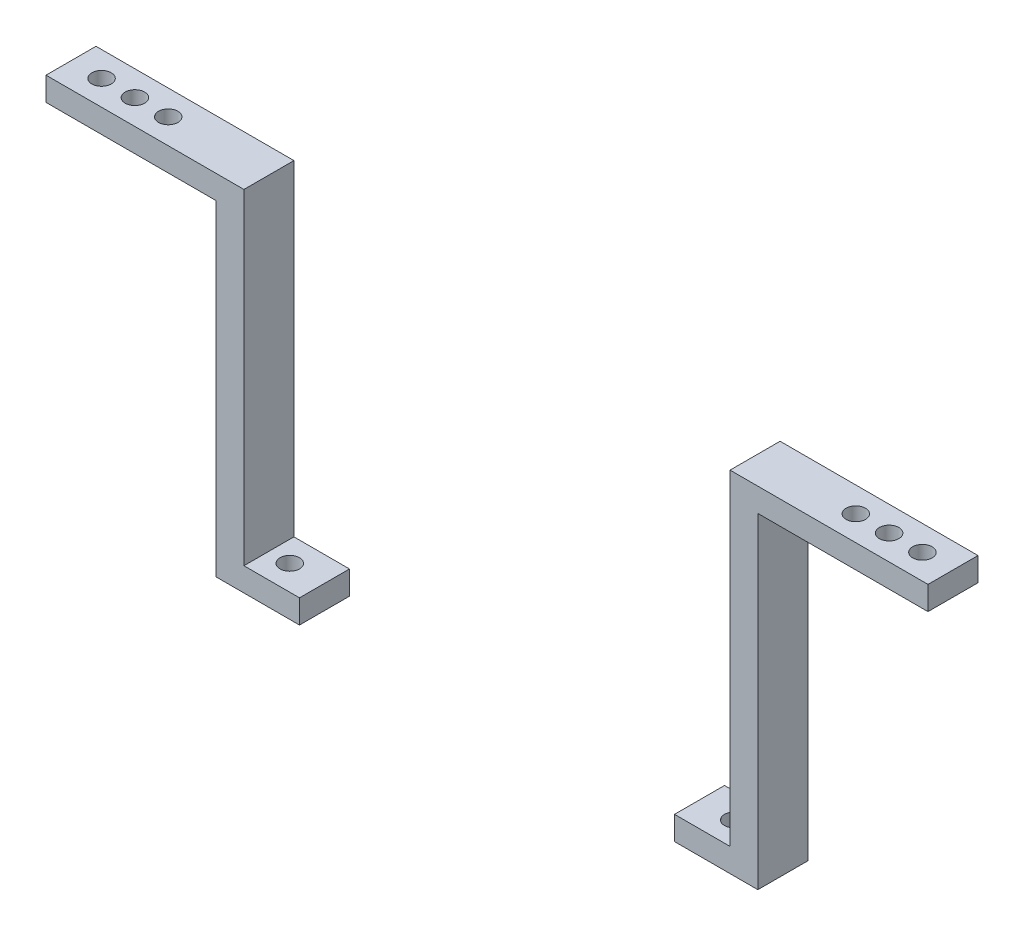
SolidWorks part; units mm, degrees
ref_plane "Front Plane" through (0, 0, 0) normal (0, 0, 1) x (1, 0, 0)
ref_plane "Top Plane" through (0, 0, 0) normal (0, 1, 0) x (1, 0, 0)
ref_plane "Right Plane" through (0, 0, 0) normal (1, 0, 0) x (0, 0, -1)
sketch "Sketch1" plane through (0, 0, 0) normal (0, 1, 0) x (1, 0, 0)
  line L0 (-34.29, 0) -> (0, 0) construction
  line L1 (-49.53, 4.572) -> (-34.29, 4.572)
  line L2 (-49.53, 4.572) -> (-49.53, -4.572)
  line L3 (-49.53, -4.572) -> (-34.29, -4.572)
  line L4 (-34.29, 4.572) -> (-34.29, -4.572)
  line L5 (34.29, 4.572) -> (49.53, 4.572)
  line L6 (34.29, 4.572) -> (34.29, -4.572)
  line L7 (34.29, -4.572) -> (49.53, -4.572)
  line L8 (49.53, 4.572) -> (49.53, -4.572)
  line L9 (0, 0) -> (34.29, 0) construction
  line L10 (-40.64, 0) -> (0, 0) construction
  line L11 (0, 0) -> (40.64, 0) construction
  line L12 (-40.64, -4.572) -> (-40.64, 0) construction
  line L14 (-40.64, 0) -> (-40.64, 4.572) construction
  circle A0 centre (-40.64, 0) radius 1.778
  circle A1 centre (40.64, 0) radius 1.778
  dimension "D2" = 3.556
  dimension "D1" = 34.29
  dimension "D3" = 40.64
  dimension "D4" = 9.144
  dimension "D5" = 8.89
  dimension "D6" = 49.53
extrude "Boss-Extrude1" add sketch "Sketch1" along normal blind 4.318
sketch "Sketch2" plane through (0, 4.318, 0) normal (0, 1, 0) x (1, 0, 0)
  line L0 (-49.53, -4.572) -> (-34.29, -4.572) construction
  line L1 (-49.53, 4.572) -> (-44.45, 4.572)
  line L2 (-49.53, 4.572) -> (-49.53, -4.572)
  line L3 (-49.53, -4.572) -> (-44.45, -4.572)
  line L4 (-44.45, 4.572) -> (-44.45, -4.572)
  line L5 (49.53, 4.572) -> (34.29, 4.572) construction
  line L6 (49.53, -4.572) -> (44.45, -4.572)
  line L7 (49.53, -4.572) -> (49.53, 4.572)
  line L8 (49.53, 4.572) -> (44.45, 4.572)
  line L9 (44.45, -4.572) -> (44.45, 4.572)
  dimension "D1" = 5.08
extrude "Boss-Extrude2" add sketch "Sketch2" along normal blind 55.276
sketch "Sketch3" plane through (0, 59.594, 0) normal (0, 1, 0) x (1, 0, 0)
  line L1 (-44.45, -4.572) -> (-80.645, -4.572)
  line L2 (-44.45, -4.572) -> (-44.45, 4.572)
  line L3 (-44.45, 4.572) -> (-80.645, 4.572)
  line L4 (-80.645, -4.572) -> (-80.645, 4.572)
  line L5 (44.45, -4.572) -> (80.645, -4.572)
  line L6 (44.45, -4.572) -> (44.45, 4.572)
  line L7 (44.45, 4.572) -> (80.645, 4.572)
  line L8 (80.645, -4.572) -> (80.645, 4.572)
extrude "Boss-Extrude3" add sketch "Sketch3" along normal blind 4.318
sketch "Sketch4" plane through (0, 63.912, 0) normal (0, 1, 0) x (1, 0, 0)
  line L0 (-75.057, 0) -> (0, 0) construction
  line L1 (0, 0) -> (75.057, 0) construction
  circle A0 centre (-75.057, 0) radius 1.778
  circle A1 centre (75.057, 0) radius 1.778
  dimension "D1" = 3.556
  dimension "D2" = 150.114
extrude "Cut-Extrude1" cut sketch "Sketch4" against normal through all
sketch "Sketch5" plane through (0, 63.912, 0) normal (0, 1, 0) x (1, 0, 0)
  line L0 (-75.057, 0) -> (-68.961, 0) construction
  line L1 (-68.961, 0) -> (-62.865, 0) construction
  line L2 (62.865, 0) -> (68.961, 0) construction
  line L3 (68.961, 0) -> (75.057, 0) construction
  circle A0 centre (-68.961, 0) radius 1.778
  circle A1 centre (-62.865, 0) radius 1.778
  circle A2 centre (62.865, 0) radius 1.778
  circle A3 centre (68.961, 0) radius 1.778
  dimension "D1" = 3.556
  dimension "D2" = 6.096
extrude "Cut-Extrude2" cut sketch "Sketch5" against normal through all
